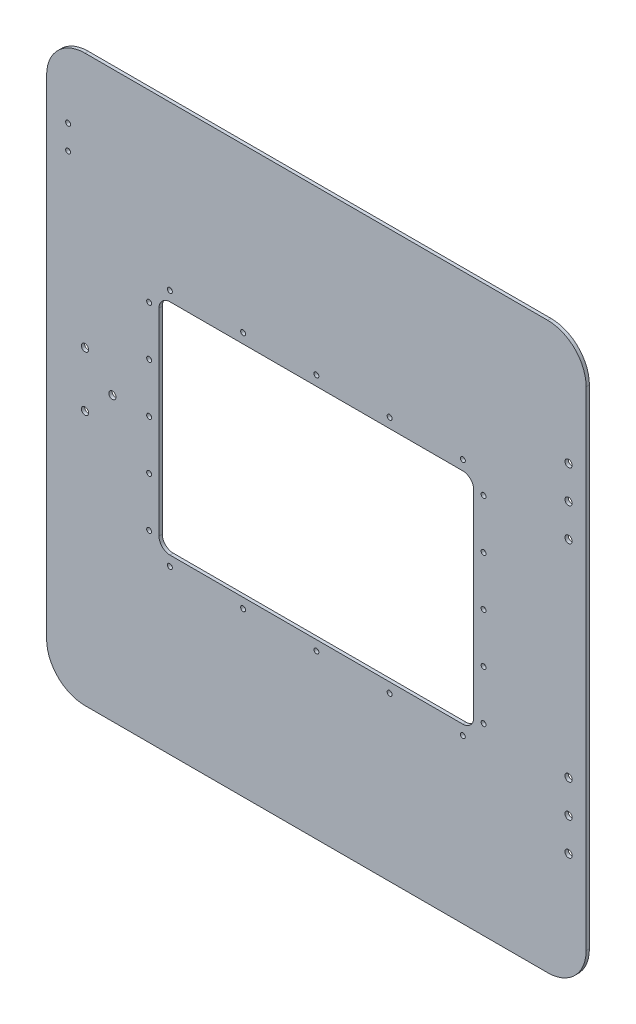
SolidWorks part; units mm, degrees
material "3.3315 (EN-AW 5005)"
ref_plane "Front Plane" through (0, 0, 0) normal (0, 0, 1) x (1, 0, 0)
ref_plane "Top Plane" through (0, 0, 0) normal (0, 1, 0) x (1, 0, 0)
ref_plane "Right Plane" through (0, 0, 0) normal (1, 0, 0) x (0, 0, -1)
sketch "Sketch1" plane through (0, 0, 0) normal (0, 0, 1) x (1, 0, 0)
  line L1 (-246, -257.65) -> (246, -257.65)
  line L2 (-246, -257.65) -> (-246, 257.65)
  line L3 (-246, 257.65) -> (246, 257.65)
  line L4 (246, -257.65) -> (246, 257.65)
  line L5 (-246, -257.65) -> (246, 257.65) construction
  line L6 (-246, 257.65) -> (246, -257.65) construction
  point P0 (0, 0)
  dimension "D1" = 515.3
  dimension "D2" = 492
extrude "Boss-Extrude1" add sketch "Sketch1" along normal mid plane 3
hole_wizard "M6 Clearance Hole1" positions "Sketch2" profile "Sketch3" hole size "M6" standard "ISO" end condition through all
sketch "Sketch2" plane through (0, 0, -1.5) normal (0, 0, -1) x (-1, 0, 0)
  line L0 (-246, -257.65) -> (-246, 257.65) construction
  line L1 (-262, 154.117) -> (-230, 154.117) construction
  line L3 (-262, 94.117) -> (-230, 94.117) construction
  line L4 (-230, 94.117) -> (-230, 124.117) construction
  line L5 (-230, 124.117) -> (-230, 154.117) construction
  line L7 (0, 0) -> (-70.8949, 0) construction
  point P0 (-230, 154.117)
  point P2 (-230, 124.117)
  point P4 (-230, 94.117)
  point P28 (-230, -94.117)
  point P29 (-230, -124.117)
  point P30 (-230, -154.117)
  dimension "D1" = 16
sketch "Sketch3" plane through (230, 154.117, -1.5) normal (1, 0, 0) x (0, 1, 0)
  line L0 (0, 0) -> (0, 3)
  line L1 (0, 3) -> (3.3, 3)
  line L2 (3.3, 3) -> (3.3, 0)
  line L5 (3.3, 0) -> (0, 0)
  line L11 (0, -6.35) -> (0, 107.95) construction
  dimension "Thru Hole Dia." = 6.6
  dimension "Thru Hole Depth" = 3
hole_wizard "M6 Clearance Hole2" positions "Sketch4" profile "Sketch5" hole size "M6" standard "ISO" end condition through all
sketch "Sketch4" plane through (0, 0, -1.5) normal (0, 0, -1) x (-1, 0, 0)
  line L0 (211, 25) -> (186, 25) construction
  line L1 (186, 25) -> (186, 0) construction
  line L3 (211, -25) -> (211, 25) construction
  line L5 (186, 0) -> (211, 0) construction
  line L7 (246, 257.65) -> (246, -257.65) construction
  line L8 (211, 0) -> (246, 0) construction
  point P0 (211, 25)
  point P2 (211, -25)
  point P4 (186, 0)
  dimension "D1" = 25
  dimension "D2" = 35
sketch "Sketch5" plane through (-211, 25, -1.5) normal (1, 0, 0) x (0, 1, 0)
  line L0 (0, 0) -> (0, 3)
  line L1 (0, 3) -> (3.3, 3)
  line L2 (3.3, 3) -> (3.3, 0)
  line L5 (3.3, 0) -> (0, 0)
  line L11 (0, -6.35) -> (0, 107.95) construction
  dimension "Thru Hole Dia." = 6.6
  dimension "Thru Hole Depth" = 3
fillet "Fillet1" radius 35 4 edges at (246, -257.65, 0) (-246, -257.65, 0) (-246, 257.65, 0) (246, 257.65, 0)
sketch "Sketch6" plane through (0, 0, -1.5) normal (0, 0, -1) x (-1, 0, 0)
  line L1 (-133.5, -100) -> (133.5, -100)
  line L2 (-143.5, -90) -> (-143.5, 90)
  line L3 (-133.5, 100) -> (133.5, 100)
  line L4 (143.5, -90) -> (143.5, 90)
  line L5 (-143.5, -100) -> (143.5, 100) construction
  line L6 (-143.5, 100) -> (143.5, -100) construction
  arc A0 (-133.5, -100) -> (-143.5, -90) centre (-133.5, -90) cw
  arc A1 (133.5, -100) -> (143.5, -90) centre (133.5, -90) ccw
  arc A2 (133.5, 100) -> (143.5, 90) centre (133.5, 90) cw
  arc A3 (-143.5, 90) -> (-133.5, 100) centre (-133.5, 90) cw
  point P0 (0, 0)
  dimension "D3" = 10
  dimension "D1" = 287
  dimension "D2" = 200
extrude "Cut-Extrude1" cut sketch "Sketch6" against normal through all
hole_wizard "M4 Clearance Hole1" positions "Sketch7" profile "Sketch8" hole size "M4" standard "ISO" end condition through all
sketch "Sketch7" plane through (0, 0, -1.5) normal (0, 0, -1) x (-1, 0, 0)
  point P0 (-133.6, -109)
  point P4 (-66.8, -109)
  point P7 (0, -109)
  point P10 (66.8, -109)
  point P13 (133.6, -109)
  point P16 (152.5, -90.1)
  point P19 (152.5, -45.05)
  point P22 (152.5, 0)
  point P25 (152.5, 45.05)
  point P28 (152.5, 90.1)
  point P31 (133.6, 109)
  point P34 (66.8, 109)
  point P37 (0, 109)
  point P40 (-66.8, 109)
  point P43 (-133.6, 109)
  point P46 (-152.5, 90.1)
  point P49 (-152.5, 45.05)
  point P52 (-152.5, 0)
  point P55 (-152.5, -45.05)
  point P58 (-152.5, -90.1)
sketch "Sketch8" plane through (133.6, -109, -1.5) normal (1, 0, 0) x (0, 1, 0)
  line L0 (0, 0) -> (0, 3)
  line L1 (0, 3) -> (2.25, 3)
  line L2 (2.25, 3) -> (2.25, 0)
  line L5 (2.25, 0) -> (0, 0)
  line L11 (0, -6.35) -> (0, 107.95) construction
  dimension "Thru Hole Dia." = 4.5
  dimension "Thru Hole Depth" = 3
hole_wizard "M4 Clearance Hole2" positions "Sketch9" profile "Sketch10" hole size "M4" standard "ISO" end condition through all
sketch "Sketch9" plane through (0, 0, -1.5) normal (0, 0, -1) x (-1, 0, 0)
  point P0 (226.4, 194.65)
  point P3 (226.4, 172.65)
sketch "Sketch10" plane through (-226.4, 194.65, -1.5) normal (1, 0, 0) x (0, 1, 0)
  line L0 (0, 0) -> (0, 3)
  line L1 (0, 3) -> (2.25, 3)
  line L2 (2.25, 3) -> (2.25, 0)
  line L5 (2.25, 0) -> (0, 0)
  line L11 (0, -6.35) -> (0, 107.95) construction
  dimension "Thru Hole Dia." = 4.5
  dimension "Thru Hole Depth" = 3
